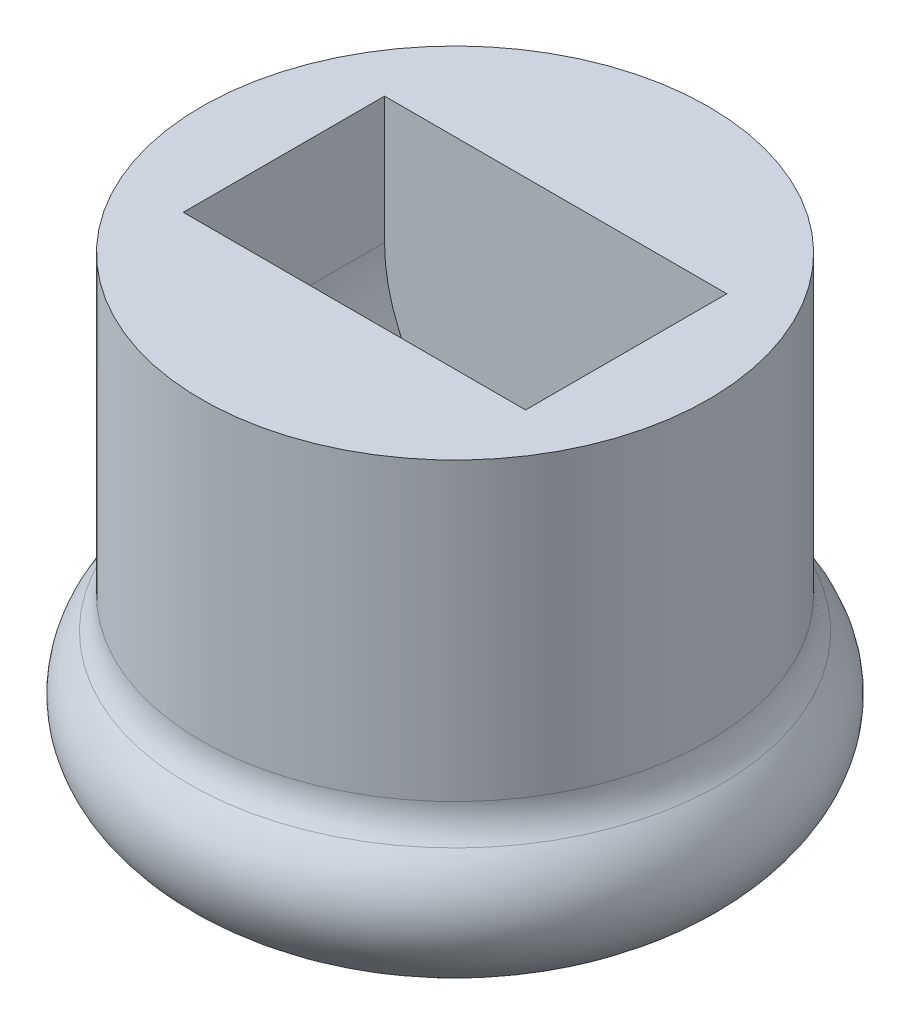
SolidWorks part; units mm, degrees
ref_plane "Front Plane" through (0, 0, 0) normal (0, 0, 1) x (1, 0, 0)
ref_plane "Top Plane" through (0, 0, 0) normal (0, 1, 0) x (1, 0, 0)
ref_plane "Right Plane" through (0, 0, 0) normal (1, 0, 0) x (0, 0, -1)
sketch "Sketch1" plane through (0, 0, 0) normal (1, 0, 0) x (0, 0, -1)
  line L0 (0, -60.7508) -> (0, 8.7698) construction
  line L1 (0, 6.0179) -> (0, 48.7101) construction
  line L3 (4, 1.3522) -> (4, 6.0179)
  line L4 (4, 6.0179) -> (0, 6.0179)
  line L6 (0, 6.0179) -> (0, -2.1766)
  arc A0 (4, 1.3522) -> (4.1902, 0.8531) centre (4.75, 1.3522) ccw
  ellipse E0 centre (0, 0) end of major axis (-4.5546, 0) minor radius 2.1766 (0, -2.1766) -> (4.1902, 0.8531) ccw
  point P5 (0, -3.4554)
  point P11 (7.5258, 0)
  point P15 (1.8542, 2.8202)
  point P17 (3.5, 2.727)
  point P18 (0, -1.8715)
  point P19 (0, 0)
  point P21 (0, -2.1766)
  point P22 (4.5546, 0)
  dimension "D1" = 0.75
  dimension "4" = 4
revolve "Revolve3" add sketch "Sketch1" angle 360 about L1
sketch "Sketch2" plane through (0, 6.0179, 0) normal (0, 1, 0) x (1, 0, 0)
  line L0 (0, 1.5875) -> (0, -1.5875) construction
  line L1 (-2.7, 1.5875) -> (2.7, 1.5875)
  line L2 (-2.7, 1.5875) -> (-2.7, -1.5875)
  line L3 (-2.7, -1.5875) -> (2.7, -1.5875)
  line L4 (2.7, 1.5875) -> (2.7, -1.5875)
  line L5 (-2.7, 0) -> (2.7, 0) construction
  dimension "D1" = 5.4
  dimension "D2" = 3.175
extrude "Cut-Extrude1" cut sketch "Sketch2" against normal blind 2
sketch "Sketch4" plane through (0, 0, -1.5875) normal (0, 0, 1) x (1, 0, 0)
  line L0 (2.7, 4.0179) -> (-2.7, 4.0179) construction
  line L1 (2.7, 4.0179) -> (-2.7, 4.0179) construction
  circle A0 centre (0, 4.0179) radius 2.7
  point P4 (0, 0)
extrude "Cut-Extrude2" cut sketch "Sketch4" along normal blind 3.175
